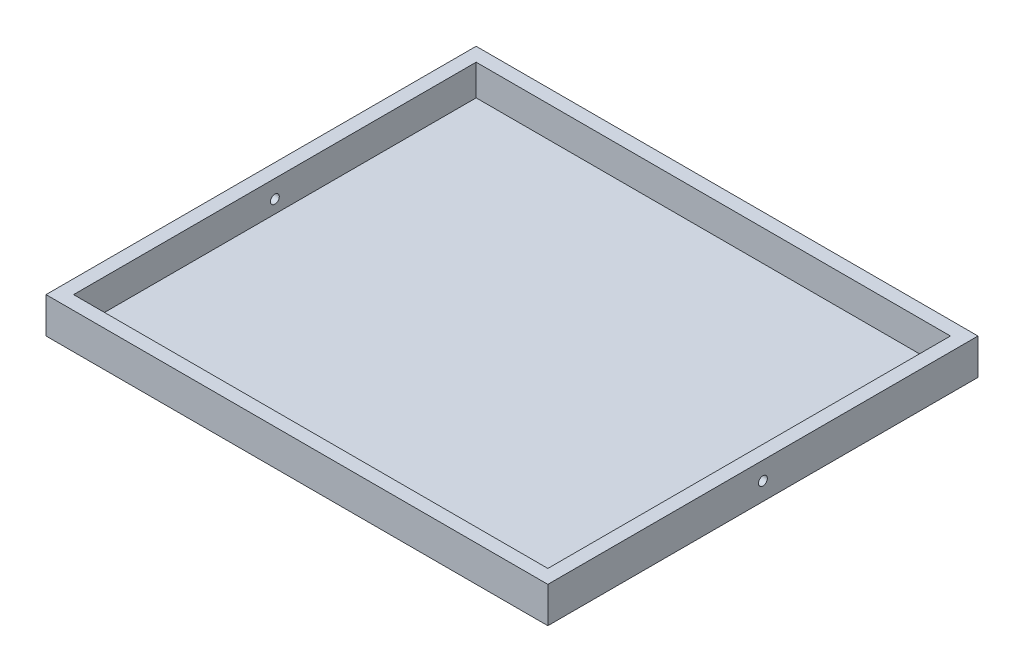
SolidWorks part; units mm, degrees
ref_plane "Front Plane" through (0, 0, 0) normal (0, 0, 1) x (1, 0, 0)
ref_plane "Top Plane" through (0, 0, 0) normal (0, 1, 0) x (1, 0, 0)
ref_plane "Right Plane" through (0, 0, 0) normal (1, 0, 0) x (0, 0, -1)
sketch "Sketch1" plane through (0, 0, 0) normal (0, 1, 0) x (1, 0, 0)
  line L1 (-97.2981, 41.3431) -> (191.6269, 41.3431)
  line L2 (-97.2981, 41.3431) -> (-97.2981, -206.3069)
  line L3 (-97.2981, -206.3069) -> (191.6269, -206.3069)
  line L4 (191.6269, 41.3431) -> (191.6269, -206.3069)
  line L5 (-89.3606, 33.4056) -> (183.6894, 33.4056)
  line L6 (-89.3606, 33.4056) -> (-89.3606, -198.3694)
  line L7 (-89.3606, -198.3694) -> (183.6894, -198.3694)
  line L8 (183.6894, 33.4056) -> (183.6894, -198.3694)
  dimension "D1" = 288.925
  dimension "D2" = 247.65
  dimension "D3" = 7.9375
  dimension "D4" = 7.9375
  dimension "D5" = 7.9375
  dimension "D6" = 7.9375
extrude "Boss-Extrude1" add sketch "Sketch1" along normal blind 20.6375
sketch "Sketch2" plane through (-89.3606, 0, 0) normal (1, 0, 0) x (0, 0, -1)
  line L0 (33.4056, 20.6375) -> (33.4056, 0) construction
  line L1 (-198.3694, 0) -> (33.4056, 0)
  line L2 (-198.3694, 0) -> (-198.3694, 2.8396)
  line L3 (-198.3694, 2.8396) -> (33.4056, 2.8396)
  line L4 (33.4056, 0) -> (33.4056, 2.8396)
extrude "Boss-Extrude2" add sketch "Sketch2" along normal up to surface (273.05 mm away) up to face at (183.6894, 10.3187, 82.4819)
sketch "Sketch3" plane through (191.6269, 0, 0) normal (1, 0, 0) x (0, 0, -1)
  line L0 (-206.3069, 10.3187) -> (41.3431, 10.3187) construction
  line L1 (-206.3069, 20.6375) -> (-206.3069, 0) construction
  line L2 (41.3431, 20.6375) -> (41.3431, 0) construction
  circle A0 centre (-82.4819, 10.3187) radius 2.54
extrude "Cut-Extrude1" cut sketch "Sketch3" against normal through all
